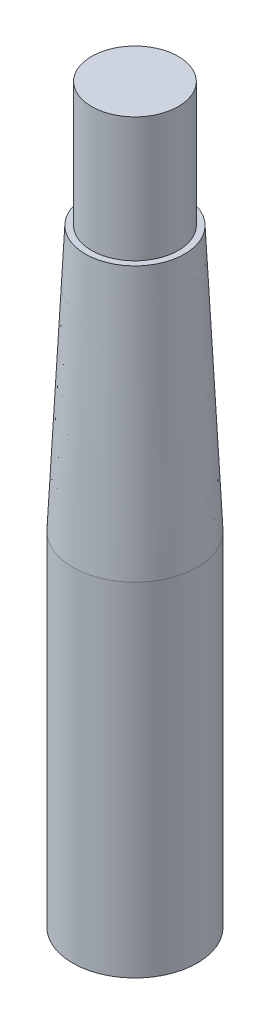
SolidWorks part; units mm, degrees
ref_plane "Front Plane" through (0, 0, 0) normal (0, 0, 1) x (1, 0, 0)
ref_plane "Top Plane" through (0, 0, 0) normal (0, 1, 0) x (1, 0, 0)
ref_plane "Right Plane" through (0, 0, 0) normal (1, 0, 0) x (0, 0, -1)
sketch "Sketch1" plane through (0, 0, 0) normal (0, 1, 0) x (1, 0, 0)
  circle A0 centre (0, 0) radius 4
  dimension "D1" = 8
extrude "Boss-Extrude1" add sketch "Sketch1" along normal blind 22
sketch "Sketch2" plane through (0, 22, 0) normal (0, 1, 0) x (1, 0, 0)
  circle A1 centre (0, 0) radius 4 construction
  circle A2 centre (0, 0) radius 4
extrude "Boss-Extrude2" add sketch "Sketch2" along normal blind 17 draft 2.75
sketch "Sketch3" plane through (0, 39, 0) normal (0, 1, 0) x (1, 0, 0)
  circle A0 centre (0, 0) radius 2.7866
  circle A1 centre (0, 0) radius 3.1834 construction
  dimension "D1" = 0.3969
extrude "Boss-Extrude3" add sketch "Sketch3" along normal blind 8
